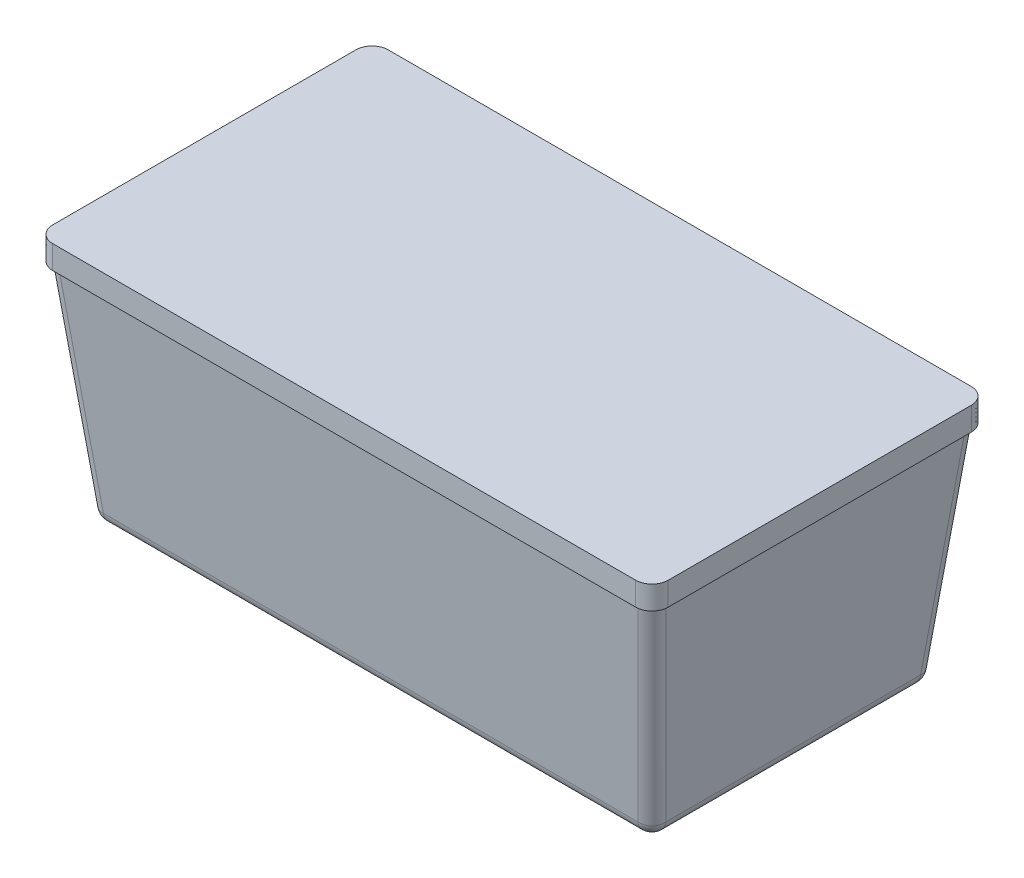
SolidWorks part; units mm, degrees
ref_plane "Alzado" through (0, 0, 0) normal (0, 0, 1) x (1, 0, 0)
ref_plane "Planta" through (0, 0, 0) normal (0, 1, 0) x (1, 0, 0)
ref_plane "Vista lateral" through (0, 0, 0) normal (1, 0, 0) x (0, 0, -1)
sketch "Croquis1" plane through (0, 0, 0) normal (0, 1, 0) x (1, 0, 0)
  line L1 (600, -300) -> (-600, -300)
  line L2 (600, -300) -> (600, 300)
  line L3 (600, 300) -> (-600, 300)
  line L4 (-600, -300) -> (-600, 300)
  line L5 (600, -300) -> (-600, 300) construction
  line L6 (600, 300) -> (-600, -300) construction
  point P0 (0, 0)
  dimension "D1" = 600
  dimension "D2" = 1200
extrude "Extruir1" add sketch "Croquis1" along normal blind 520 draft 6 draft outward yes
fillet "Redondeo1" radius 30 8 edges at (0, 0, 300) (600, 0, 0) (0, 0, -300) (-600, 0, 0) (-627.3271, 260, -327.3271) (627.3271, 260, -327.3271) (627.3271, 260, 327.3271) (-627.3271, 260, 327.3271)
shell "Vaciado1" thickness 10
sketch "Croquis2" plane through (0, 520, 0) normal (0, 1, 0) x (1, 0, 0)
  line L24 (624.8185, 359.6542) -> (-624.8185, 359.6542)
  line L25 (659.6542, -324.8185) -> (659.6542, 324.8185)
  line L26 (-624.8185, -359.6542) -> (624.8185, -359.6542)
  line L27 (-659.6542, 324.8185) -> (-659.6542, -324.8185)
  line L28 (624.8185, 359.6542) -> (-624.8185, 359.6542)
  line L29 (659.6542, -324.8185) -> (659.6542, 324.8185)
  line L30 (-624.8185, -359.6542) -> (624.8185, -359.6542)
  line L31 (-659.6542, 324.8185) -> (-659.6542, -324.8185)
  spline S0 degree 3 poles (9.626, -1532.0878) (-367.9234, -0.852) (-535.9095, 377.862) (-632.7137, 358.7732) (-633.8149, 358.5002) (-635.4515, 358.0079) (-635.9946, 357.83) (-637.0755, 357.446) (-637.6138, 357.2397) (-640.2615, 356.1489) (-642.2653, 355.0812) (-645.1032, 353.1931) (-646.0209, 352.5157) (-647.3539, 351.425) (-647.7906, 351.0493) (-648.6395, 350.2812) (-649.053, 349.888) (-651.067, 347.8765) (-652.5079, 346.1233) (-654.4118, 343.2761) (-655.0058, 342.2851) (-656.0832, 340.2672) (-656.5688, 339.238) (-657.8704, 336.0912) (-658.5327, 333.9145) (-684.6397, 202.615) (24.9986, 1.0365) (1249.82, -251.3643) knots -5.25859 -5.25859 -5.25859 -5.25859 0.125 0.125 0.1875 0.1875 0.21875 0.21875 0.25 0.25 0.375 0.375 0.4375 0.4375 0.46875 0.46875 0.5 0.5 0.625 0.625 0.6875 0.6875 0.75 0.75 0.875 0.875 8.020589 8.020589 8.020589 8.020589 only from (-624.8185, 359.6542) to (-659.6542, 324.8185)
  spline S1 degree 3 poles (-1232.0878, -309.626) (299.148, 67.9234) (677.862, 235.9095) (658.7732, 332.7137) (658.5002, 333.8149) (658.0079, 335.4515) (657.83, 335.9946) (657.446, 337.0755) (657.2397, 337.6138) (656.1489, 340.2615) (655.0812, 342.2653) (653.1931, 345.1032) (652.5157, 346.0209) (651.425, 347.3539) (651.0493, 347.7906) (650.2812, 348.6395) (649.888, 349.053) (647.8765, 351.067) (646.1233, 352.5079) (643.2761, 354.4118) (642.2851, 355.0058) (640.2672, 356.0832) (639.238, 356.5688) (636.0912, 357.8704) (633.9145, 358.5327) (502.615, 384.6397) (301.0365, -324.9986) (48.6357, -1549.82) knots -5.25859 -5.25859 -5.25859 -5.25859 0.125 0.125 0.1875 0.1875 0.21875 0.21875 0.25 0.25 0.375 0.375 0.4375 0.4375 0.46875 0.46875 0.5 0.5 0.625 0.625 0.6875 0.6875 0.75 0.75 0.875 0.875 8.020589 8.020589 8.020589 8.020589 only from (659.6542, 324.8185) to (624.8185, 359.6542)
  spline S2 degree 3 poles (-9.626, 1532.0878) (367.9234, 0.852) (535.9095, -377.862) (632.7137, -358.7732) (633.8149, -358.5002) (635.4515, -358.0079) (635.9946, -357.83) (637.0755, -357.446) (637.6138, -357.2397) (640.2615, -356.1489) (642.2653, -355.0812) (645.1032, -353.1931) (646.0209, -352.5157) (647.3539, -351.425) (647.7906, -351.0493) (648.6395, -350.2812) (649.053, -349.888) (651.067, -347.8765) (652.5079, -346.1233) (654.4118, -343.2761) (655.0058, -342.2851) (656.0832, -340.2672) (656.5688, -339.238) (657.8704, -336.0912) (658.5327, -333.9145) (684.6397, -202.615) (-24.9986, -1.0365) (-1249.82, 251.3643) knots -5.25859 -5.25859 -5.25859 -5.25859 0.125 0.125 0.1875 0.1875 0.21875 0.21875 0.25 0.25 0.375 0.375 0.4375 0.4375 0.46875 0.46875 0.5 0.5 0.625 0.625 0.6875 0.6875 0.75 0.75 0.875 0.875 8.020589 8.020589 8.020589 8.020589 only from (624.8185, -359.6542) to (659.6542, -324.8185)
  spline S3 degree 3 poles (1232.0878, 309.626) (-299.148, -67.9234) (-677.862, -235.9095) (-658.7732, -332.7137) (-658.5002, -333.8149) (-658.0079, -335.4515) (-657.83, -335.9946) (-657.446, -337.0755) (-657.2397, -337.6138) (-656.1489, -340.2615) (-655.0812, -342.2653) (-653.1931, -345.1032) (-652.5157, -346.0209) (-651.425, -347.3539) (-651.0493, -347.7906) (-650.2812, -348.6395) (-649.888, -349.053) (-647.8765, -351.067) (-646.1233, -352.5079) (-643.2761, -354.4118) (-642.2851, -355.0058) (-640.2672, -356.0832) (-639.238, -356.5688) (-636.0912, -357.8704) (-633.9145, -358.5327) (-502.615, -384.6397) (-301.0365, 324.9986) (-48.6357, 1549.82) knots -5.25859 -5.25859 -5.25859 -5.25859 0.125 0.125 0.1875 0.1875 0.21875 0.21875 0.25 0.25 0.375 0.375 0.4375 0.4375 0.46875 0.46875 0.5 0.5 0.625 0.625 0.6875 0.6875 0.75 0.75 0.875 0.875 8.020589 8.020589 8.020589 8.020589 only from (-659.6542, -324.8185) to (-624.8185, -359.6542)
  spline S4 degree 3 poles (-624.8185, 359.6542) (-627.1201, 359.6542) (-629.3809, 359.4304) (-632.7137, 358.7732) (-633.8149, 358.5002) (-635.4515, 358.0079) (-635.9946, 357.83) (-637.0755, 357.446) (-637.6138, 357.2397) (-640.2615, 356.1489) (-642.2653, 355.0812) (-645.1032, 353.1931) (-646.0209, 352.5157) (-647.3539, 351.425) (-647.7906, 351.0493) (-648.6395, 350.2812) (-649.053, 349.888) (-651.067, 347.8765) (-652.5079, 346.1233) (-654.4118, 343.2761) (-655.0058, 342.2851) (-656.0832, 340.2672) (-656.5688, 339.238) (-657.8704, 336.0912) (-658.5327, 333.9145) (-659.4304, 329.3998) (-659.6542, 327.1202) (-659.6542, 324.8185) knots 0 0 0 0 0.125 0.125 0.1875 0.1875 0.21875 0.21875 0.25 0.25 0.375 0.375 0.4375 0.4375 0.46875 0.46875 0.5 0.5 0.625 0.625 0.6875 0.6875 0.75 0.75 0.875 0.875 1 1 1 1
  spline S5 degree 3 poles (659.6542, 324.8185) (659.6542, 327.1201) (659.4304, 329.3809) (658.7732, 332.7137) (658.5002, 333.8149) (658.0079, 335.4515) (657.83, 335.9946) (657.446, 337.0755) (657.2397, 337.6138) (656.1489, 340.2615) (655.0812, 342.2653) (653.1931, 345.1032) (652.5157, 346.0209) (651.425, 347.3539) (651.0493, 347.7906) (650.2812, 348.6395) (649.888, 349.053) (647.8765, 351.067) (646.1233, 352.5079) (643.2761, 354.4118) (642.2851, 355.0058) (640.2672, 356.0832) (639.238, 356.5688) (636.0912, 357.8704) (633.9145, 358.5327) (629.3998, 359.4304) (627.1202, 359.6542) (624.8185, 359.6542) knots 0 0 0 0 0.125 0.125 0.1875 0.1875 0.21875 0.21875 0.25 0.25 0.375 0.375 0.4375 0.4375 0.46875 0.46875 0.5 0.5 0.625 0.625 0.6875 0.6875 0.75 0.75 0.875 0.875 1 1 1 1
  spline S6 degree 3 poles (624.8185, -359.6542) (627.1201, -359.6542) (629.3809, -359.4304) (632.7137, -358.7732) (633.8149, -358.5002) (635.4515, -358.0079) (635.9946, -357.83) (637.0755, -357.446) (637.6138, -357.2397) (640.2615, -356.1489) (642.2653, -355.0812) (645.1032, -353.1931) (646.0209, -352.5157) (647.3539, -351.425) (647.7906, -351.0493) (648.6395, -350.2812) (649.053, -349.888) (651.067, -347.8765) (652.5079, -346.1233) (654.4118, -343.2761) (655.0058, -342.2851) (656.0832, -340.2672) (656.5688, -339.238) (657.8704, -336.0912) (658.5327, -333.9145) (659.4304, -329.3998) (659.6542, -327.1202) (659.6542, -324.8185) knots 0 0 0 0 0.125 0.125 0.1875 0.1875 0.21875 0.21875 0.25 0.25 0.375 0.375 0.4375 0.4375 0.46875 0.46875 0.5 0.5 0.625 0.625 0.6875 0.6875 0.75 0.75 0.875 0.875 1 1 1 1
  spline S7 degree 3 poles (-659.6542, -324.8185) (-659.6542, -327.1201) (-659.4304, -329.3809) (-658.7732, -332.7137) (-658.5002, -333.8149) (-658.0079, -335.4515) (-657.83, -335.9946) (-657.446, -337.0755) (-657.2397, -337.6138) (-656.1489, -340.2615) (-655.0812, -342.2653) (-653.1931, -345.1032) (-652.5157, -346.0209) (-651.425, -347.3539) (-651.0493, -347.7906) (-650.2812, -348.6395) (-649.888, -349.053) (-647.8765, -351.067) (-646.1233, -352.5079) (-643.2761, -354.4118) (-642.2851, -355.0058) (-640.2672, -356.0832) (-639.238, -356.5688) (-636.0912, -357.8704) (-633.9145, -358.5327) (-629.3998, -359.4304) (-627.1202, -359.6542) (-624.8185, -359.6542) knots 0 0 0 0 0.125 0.125 0.1875 0.1875 0.21875 0.21875 0.25 0.25 0.375 0.375 0.4375 0.4375 0.46875 0.46875 0.5 0.5 0.625 0.625 0.6875 0.6875 0.75 0.75 0.875 0.875 1 1 1 1
  dimension "D1" = 5
extrude "Extruir2" add sketch "Croquis2" against normal blind 40 separate body
sketch "Croquis3" plane through (0, 520, 0) normal (0, 1, 0) x (1, 0, 0)
  line L4 (-659.6542, 324.8185) -> (-659.6542, -324.8185)
  line L5 (-624.8185, -359.6542) -> (624.8185, -359.6542)
  line L6 (659.6542, -324.8185) -> (659.6542, 324.8185)
  line L7 (624.8185, 359.6542) -> (-624.8185, 359.6542)
  line L8 (-659.6542, 324.8185) -> (-659.6542, -324.8185)
  line L9 (-624.8185, -359.6542) -> (624.8185, -359.6542)
  line L10 (659.6542, -324.8185) -> (659.6542, 324.8185)
  line L11 (624.8185, 359.6542) -> (-624.8185, 359.6542)
  spline S4 degree 3 poles (9.626, -1532.0878) (-367.9234, -0.852) (-535.9095, 377.862) (-632.7137, 358.7732) (-633.8149, 358.5002) (-635.4515, 358.0079) (-635.9946, 357.83) (-637.0755, 357.446) (-637.6138, 357.2397) (-640.2615, 356.1489) (-642.2653, 355.0812) (-645.1032, 353.1931) (-646.0209, 352.5157) (-647.3539, 351.425) (-647.7906, 351.0493) (-648.6395, 350.2812) (-649.053, 349.888) (-651.067, 347.8765) (-652.5079, 346.1233) (-654.4118, 343.2761) (-655.0058, 342.2851) (-656.0832, 340.2672) (-656.5688, 339.238) (-657.8704, 336.0912) (-658.5327, 333.9145) (-684.6397, 202.615) (24.9986, 1.0365) (1249.82, -251.3643) knots -5.25859 -5.25859 -5.25859 -5.25859 0.125 0.125 0.1875 0.1875 0.21875 0.21875 0.25 0.25 0.375 0.375 0.4375 0.4375 0.46875 0.46875 0.5 0.5 0.625 0.625 0.6875 0.6875 0.75 0.75 0.875 0.875 8.020589 8.020589 8.020589 8.020589 only from (-624.8185, 359.6542) to (-659.6542, 324.8185)
  spline S5 degree 3 poles (1232.0878, 309.626) (-299.148, -67.9234) (-677.862, -235.9095) (-658.7732, -332.7137) (-658.5002, -333.8149) (-658.0079, -335.4515) (-657.83, -335.9946) (-657.446, -337.0755) (-657.2397, -337.6138) (-656.1489, -340.2615) (-655.0812, -342.2653) (-653.1931, -345.1032) (-652.5157, -346.0209) (-651.425, -347.3539) (-651.0493, -347.7906) (-650.2812, -348.6395) (-649.888, -349.053) (-647.8765, -351.067) (-646.1233, -352.5079) (-643.2761, -354.4118) (-642.2851, -355.0058) (-640.2672, -356.0832) (-639.238, -356.5688) (-636.0912, -357.8704) (-633.9145, -358.5327) (-502.615, -384.6397) (-301.0365, 324.9986) (-48.6357, 1549.82) knots -5.25859 -5.25859 -5.25859 -5.25859 0.125 0.125 0.1875 0.1875 0.21875 0.21875 0.25 0.25 0.375 0.375 0.4375 0.4375 0.46875 0.46875 0.5 0.5 0.625 0.625 0.6875 0.6875 0.75 0.75 0.875 0.875 8.020589 8.020589 8.020589 8.020589 only from (-659.6542, -324.8185) to (-624.8185, -359.6542)
  spline S6 degree 3 poles (-9.626, 1532.0878) (367.9234, 0.852) (535.9095, -377.862) (632.7137, -358.7732) (633.8149, -358.5002) (635.4515, -358.0079) (635.9946, -357.83) (637.0755, -357.446) (637.6138, -357.2397) (640.2615, -356.1489) (642.2653, -355.0812) (645.1032, -353.1931) (646.0209, -352.5157) (647.3539, -351.425) (647.7906, -351.0493) (648.6395, -350.2812) (649.053, -349.888) (651.067, -347.8765) (652.5079, -346.1233) (654.4118, -343.2761) (655.0058, -342.2851) (656.0832, -340.2672) (656.5688, -339.238) (657.8704, -336.0912) (658.5327, -333.9145) (684.6397, -202.615) (-24.9986, -1.0365) (-1249.82, 251.3643) knots -5.25859 -5.25859 -5.25859 -5.25859 0.125 0.125 0.1875 0.1875 0.21875 0.21875 0.25 0.25 0.375 0.375 0.4375 0.4375 0.46875 0.46875 0.5 0.5 0.625 0.625 0.6875 0.6875 0.75 0.75 0.875 0.875 8.020589 8.020589 8.020589 8.020589 only from (624.8185, -359.6542) to (659.6542, -324.8185)
  spline S7 degree 3 poles (-1232.0878, -309.626) (299.148, 67.9234) (677.862, 235.9095) (658.7732, 332.7137) (658.5002, 333.8149) (658.0079, 335.4515) (657.83, 335.9946) (657.446, 337.0755) (657.2397, 337.6138) (656.1489, 340.2615) (655.0812, 342.2653) (653.1931, 345.1032) (652.5157, 346.0209) (651.425, 347.3539) (651.0493, 347.7906) (650.2812, 348.6395) (649.888, 349.053) (647.8765, 351.067) (646.1233, 352.5079) (643.2761, 354.4118) (642.2851, 355.0058) (640.2672, 356.0832) (639.238, 356.5688) (636.0912, 357.8704) (633.9145, 358.5327) (502.615, 384.6397) (301.0365, -324.9986) (48.6357, -1549.82) knots -5.25859 -5.25859 -5.25859 -5.25859 0.125 0.125 0.1875 0.1875 0.21875 0.21875 0.25 0.25 0.375 0.375 0.4375 0.4375 0.46875 0.46875 0.5 0.5 0.625 0.625 0.6875 0.6875 0.75 0.75 0.875 0.875 8.020589 8.020589 8.020589 8.020589 only from (659.6542, 324.8185) to (624.8185, 359.6542)
  spline S8 degree 3 poles (-624.8185, 359.6542) (-627.1201, 359.6542) (-629.3809, 359.4304) (-632.7137, 358.7732) (-633.8149, 358.5002) (-635.4515, 358.0079) (-635.9946, 357.83) (-637.0755, 357.446) (-637.6138, 357.2397) (-640.2615, 356.1489) (-642.2653, 355.0812) (-645.1032, 353.1931) (-646.0209, 352.5157) (-647.3539, 351.425) (-647.7906, 351.0493) (-648.6395, 350.2812) (-649.053, 349.888) (-651.067, 347.8765) (-652.5079, 346.1233) (-654.4118, 343.2761) (-655.0058, 342.2851) (-656.0832, 340.2672) (-656.5688, 339.238) (-657.8704, 336.0912) (-658.5327, 333.9145) (-659.4304, 329.3998) (-659.6542, 327.1202) (-659.6542, 324.8185) knots 0 0 0 0 0.125 0.125 0.1875 0.1875 0.21875 0.21875 0.25 0.25 0.375 0.375 0.4375 0.4375 0.46875 0.46875 0.5 0.5 0.625 0.625 0.6875 0.6875 0.75 0.75 0.875 0.875 1 1 1 1
  spline S9 degree 3 poles (-659.6542, -324.8185) (-659.6542, -327.1201) (-659.4304, -329.3809) (-658.7732, -332.7137) (-658.5002, -333.8149) (-658.0079, -335.4515) (-657.83, -335.9946) (-657.446, -337.0755) (-657.2397, -337.6138) (-656.1489, -340.2615) (-655.0812, -342.2653) (-653.1931, -345.1032) (-652.5157, -346.0209) (-651.425, -347.3539) (-651.0493, -347.7906) (-650.2812, -348.6395) (-649.888, -349.053) (-647.8765, -351.067) (-646.1233, -352.5079) (-643.2761, -354.4118) (-642.2851, -355.0058) (-640.2672, -356.0832) (-639.238, -356.5688) (-636.0912, -357.8704) (-633.9145, -358.5327) (-629.3998, -359.4304) (-627.1202, -359.6542) (-624.8185, -359.6542) knots 0 0 0 0 0.125 0.125 0.1875 0.1875 0.21875 0.21875 0.25 0.25 0.375 0.375 0.4375 0.4375 0.46875 0.46875 0.5 0.5 0.625 0.625 0.6875 0.6875 0.75 0.75 0.875 0.875 1 1 1 1
  spline S10 degree 3 poles (624.8185, -359.6542) (627.1201, -359.6542) (629.3809, -359.4304) (632.7137, -358.7732) (633.8149, -358.5002) (635.4515, -358.0079) (635.9946, -357.83) (637.0755, -357.446) (637.6138, -357.2397) (640.2615, -356.1489) (642.2653, -355.0812) (645.1032, -353.1931) (646.0209, -352.5157) (647.3539, -351.425) (647.7906, -351.0493) (648.6395, -350.2812) (649.053, -349.888) (651.067, -347.8765) (652.5079, -346.1233) (654.4118, -343.2761) (655.0058, -342.2851) (656.0832, -340.2672) (656.5688, -339.238) (657.8704, -336.0912) (658.5327, -333.9145) (659.4304, -329.3998) (659.6542, -327.1202) (659.6542, -324.8185) knots 0 0 0 0 0.125 0.125 0.1875 0.1875 0.21875 0.21875 0.25 0.25 0.375 0.375 0.4375 0.4375 0.46875 0.46875 0.5 0.5 0.625 0.625 0.6875 0.6875 0.75 0.75 0.875 0.875 1 1 1 1
  spline S11 degree 3 poles (659.6542, 324.8185) (659.6542, 327.1201) (659.4304, 329.3809) (658.7732, 332.7137) (658.5002, 333.8149) (658.0079, 335.4515) (657.83, 335.9946) (657.446, 337.0755) (657.2397, 337.6138) (656.1489, 340.2615) (655.0812, 342.2653) (653.1931, 345.1032) (652.5157, 346.0209) (651.425, 347.3539) (651.0493, 347.7906) (650.2812, 348.6395) (649.888, 349.053) (647.8765, 351.067) (646.1233, 352.5079) (643.2761, 354.4118) (642.2851, 355.0058) (640.2672, 356.0832) (639.238, 356.5688) (636.0912, 357.8704) (633.9145, 358.5327) (629.3998, 359.4304) (627.1202, 359.6542) (624.8185, 359.6542) knots 0 0 0 0 0.125 0.125 0.1875 0.1875 0.21875 0.21875 0.25 0.25 0.375 0.375 0.4375 0.4375 0.46875 0.46875 0.5 0.5 0.625 0.625 0.6875 0.6875 0.75 0.75 0.875 0.875 1 1 1 1
  dimension "D1" = 0
extrude "Extruir3" add sketch "Croquis3" along normal blind 10
